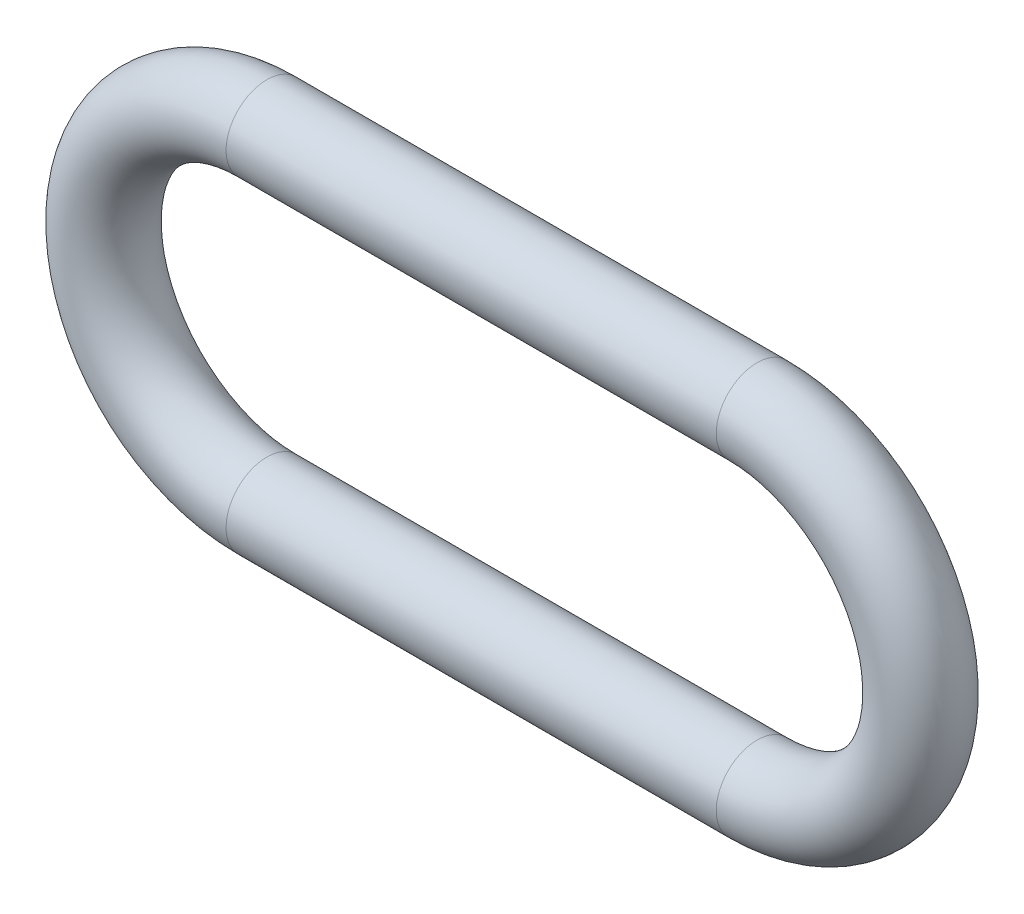
SolidWorks part; units mm, degrees
ref_plane "前视基准面" through (0, 0, 0) normal (0, 0, 1) x (1, 0, 0)
ref_plane "上视基准面" through (0, 0, 0) normal (0, 1, 0) x (1, 0, 0)
ref_plane "右视基准面" through (0, 0, 0) normal (1, 0, 0) x (0, 0, -1)
other "Configuration Table"
sketch "草图1" plane through (0, 0, 0) normal (0, 0, 1) x (1, 0, 0)
  line L1 (-6, -4) -> (6, -4)
  line L2 (-6, -4) -> (-6, 4) construction
  line L3 (-6, 4) -> (6, 4)
  line L4 (6, -4) -> (6, 4) construction
  line L5 (-6, -4) -> (6, 4) construction
  line L6 (-6, 4) -> (6, -4) construction
  arc A0 (-6, -4) -> (-6, 4) centre (-6, 0) cw
  arc A1 (6, -4) -> (6, 4) centre (6, 0) ccw
  point P0 (0, 0)
  point P6 (-10, 0)
  point P9 (10, 0)
  dimension "D1" = 20
  dimension "D2" = 8
sweep "扫描1" add path "草图1" circular profile diameter 2 parameters "D3"=2
sketch "草图3" plane through (0, 0, 0) normal (0, 1, 0) x (1, 0, 0)
  line L0 (0, 8.0886) -> (0, -6.8533) construction
  line L1 (6, -1) -> (10, -1) construction
  circle A1 centre (10, 0) radius 1
  circle A2 centre (-10, 0) radius 1
  dimension "D1" = 2
  dimension "D2" = 10
